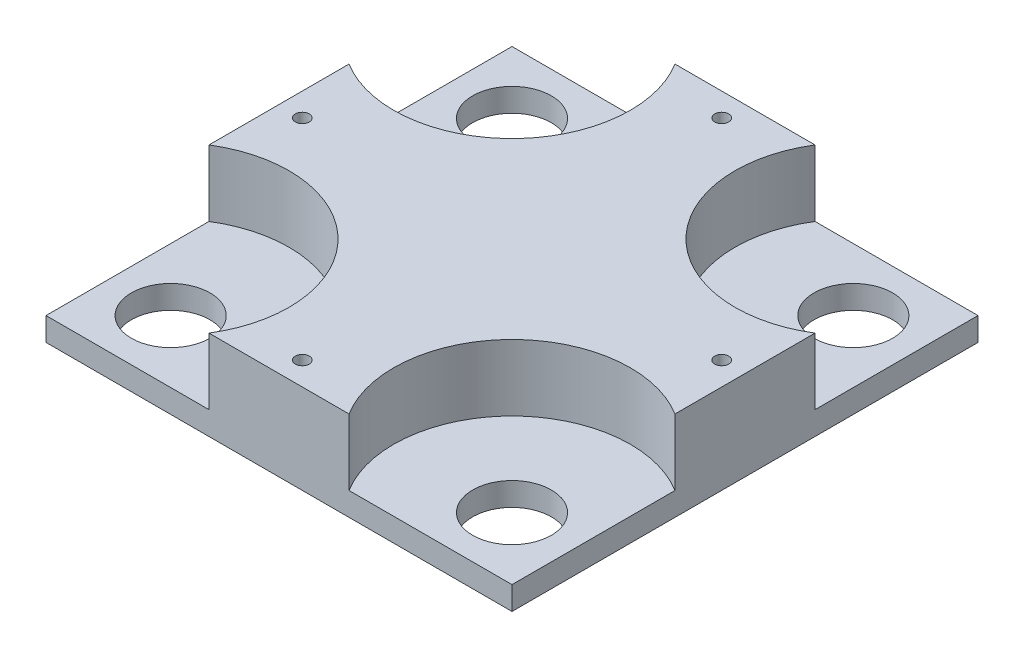
SolidWorks part; units mm, degrees
ref_plane "Front Plane" through (0, 0, 0) normal (0, 0, 1) x (1, 0, 0)
ref_plane "Top Plane" through (0, 0, 0) normal (0, 1, 0) x (1, 0, 0)
ref_plane "Right Plane" through (0, 0, 0) normal (1, 0, 0) x (0, 0, -1)
sketch "Sketch1" plane through (0, 0, 0) normal (0, 1, 0) x (1, 0, 0)
  line L0 (-13.375, 36.625) -> (86.625, 36.625) construction
  line L1 (-13.375, 86.625) -> (86.625, 86.625)
  line L2 (-13.375, 86.625) -> (-13.375, -13.375)
  line L3 (-13.375, -13.375) -> (86.625, -13.375)
  line L4 (86.625, 86.625) -> (86.625, -13.375)
  circle A3 centre (0, 0) radius 13.375 construction
  circle A6 centre (0, 0) radius 8.4375
  circle A7 centre (0, 73.25) radius 8.4375
  circle A8 centre (73.25, 73.25) radius 8.4375
  circle A9 centre (73.25, 0) radius 8.4375
  point P10 (36.625, 36.625)
  point P11 (54.9105, 80.3112)
  point P12 (36.625, 36.625)
  point P20 (36.625, 36.625)
  point P21 (36.625, 36.625)
  dimension "D3" = 26.75
  dimension "D5" = 4
  dimension "D4" = 16.875
  dimension "D1" = 100
  dimension "D2" = 100
extrude "Boss-Extrude1" add sketch "Sketch1" along normal blind 19.224
sketch "Sketch4" plane through (0, 19.224, 0) normal (0, 1, 0) x (1, 0, 0)
  line L18 (73.25, 73.25) -> (0, 73.25) construction
  line L19 (73.25, 73.25) -> (73.25, 0) construction
  line L20 (73.25, 0) -> (0, 0) construction
  line L21 (0, 73.25) -> (0, 0) construction
  circle A4 centre (0, 0) radius 25.4
  circle A5 centre (73.25, 0) radius 25.4
  circle A6 centre (73.25, 73.25) radius 25.4
  circle A7 centre (0, 73.25) radius 25.4
  point P10 (73.25, 73.25)
  dimension "D1" = 50.8
extrude "Cut-Extrude2" cut sketch "Sketch4" against normal blind 14.224
sketch "Sketch3" plane through (0, 0, 0) normal (0, 1, 0) x (1, 0, 0)
  line L0 (51.6567, 86.625) -> (21.5933, 86.625) construction
  line L1 (-13.375, 51.6567) -> (-13.375, 21.5933) construction
  line L2 (-13.375, -13.375) -> (21.5933, -13.375) construction
  circle A0 centre (36.625, 81.625) radius 1.5
  circle A1 centre (81.625, 36.625) radius 1.5
  circle A2 centre (36.625, -8.375) radius 1.5
  circle A3 centre (-8.375, 36.625) radius 1.5
  point P1 (33.2235, 35.3558)
  point P6 (36.625, 36.625)
  point P8 (36.625, 36.3243)
  point P9 (36.625, 37.3864)
  point P10 (36.625, 43.8768)
  point P21 (36.625, 36.625)
  dimension "D3" = 3
  dimension "D1" = 5
  dimension "D2" = 50
  dimension "D5" = 50
  dimension "D4" = 4
extrude "Cut-Extrude1" cut sketch "Sketch3" along normal through all both and the other way through all
